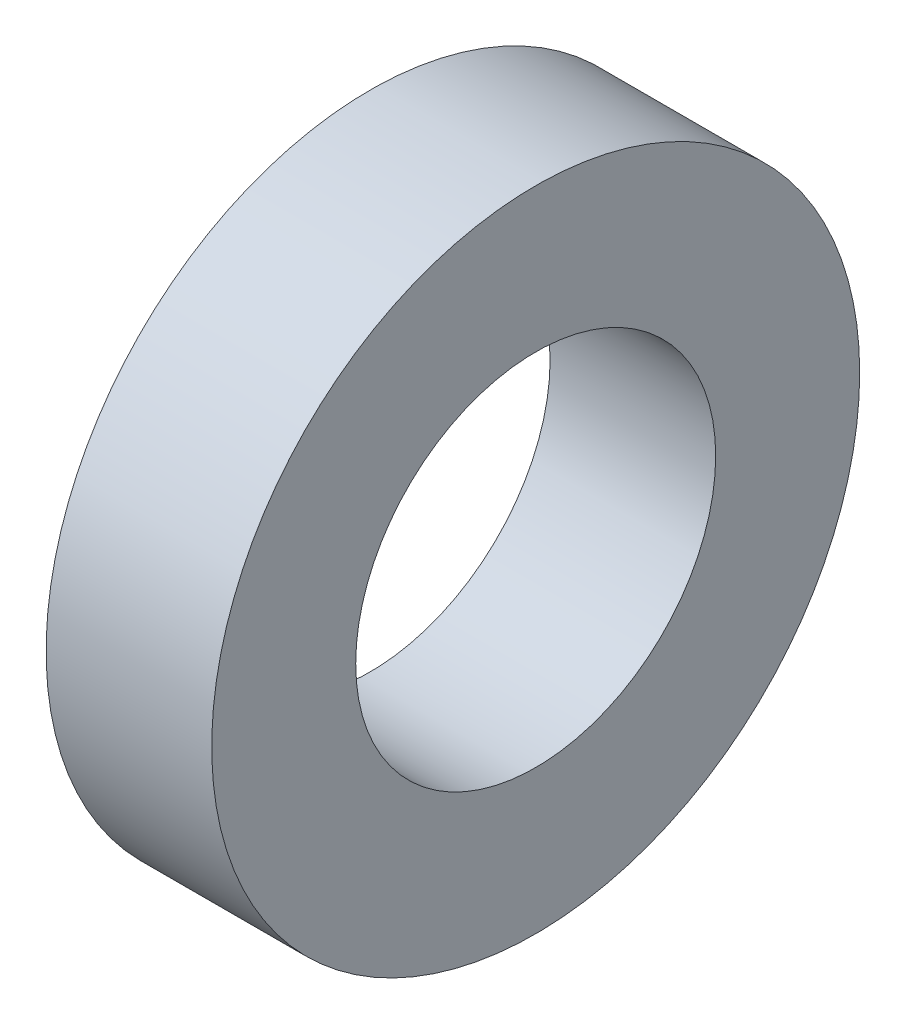
SolidWorks part; units mm, degrees
ref_plane "Спереди" through (0, 0, 0) normal (0, 0, 1) x (1, 0, 0)
ref_plane "Сверху" through (0, 0, 0) normal (0, 1, 0) x (1, 0, 0)
ref_plane "Справа" through (0, 0, 0) normal (1, 0, 0) x (0, 0, -1)
sketch "Эскиз1" plane through (0, 0, 0) normal (0, 0, 1) x (1, 0, 0)
  line L0 (0, 0) -> (-71372.4782, 0) construction
  line L1 (0, 0) -> (0, 71372.4782) construction
  line L2 (-11.5, 45) -> (11.5, 45)
  line L3 (-11.5, 45) -> (-11.5, 25)
  line L4 (-11.5, 25) -> (11.5, 25)
  line L5 (11.5, 45) -> (11.5, 25)
  dimension "D1" = 50
  dimension "D2" = 90
  dimension "D3" = 23
revolve "Повернуть1" add sketch "Эскиз1" angle 360 about L0
